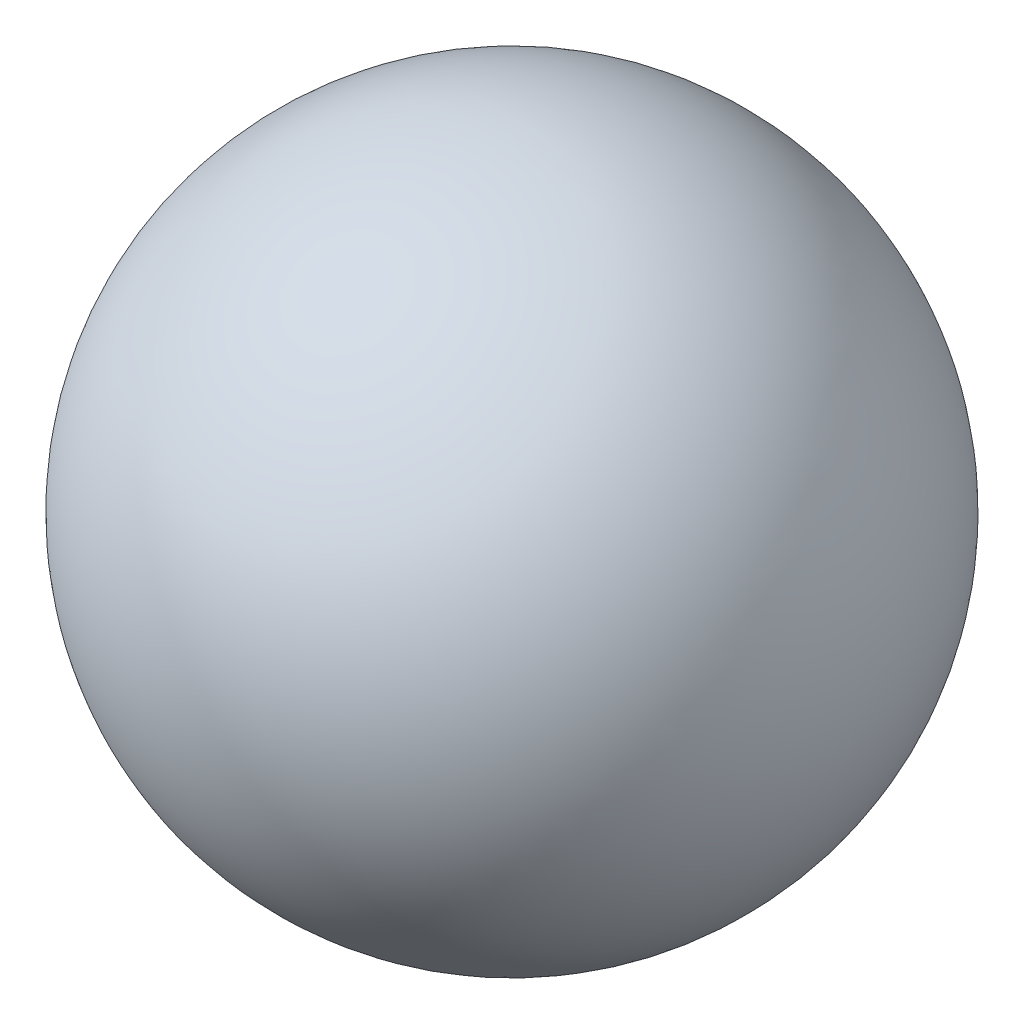
SolidWorks part; units mm, degrees
ref_plane "Front Plane" through (0, 0, 0) normal (0, 0, 1) x (1, 0, 0)
ref_plane "Top Plane" through (0, 0, 0) normal (0, 1, 0) x (1, 0, 0)
ref_plane "Right Plane" through (0, 0, 0) normal (1, 0, 0) x (0, 0, -1)
sketch "Sketch1" plane through (0, 0, 0) normal (0, 1, 0) x (1, 0, 0)
  line L0 (0, 7) -> (0, -7) construction
  circle A0 centre (0, 0) radius 7
  dimension "D1" = 14
revolve "Revolve2" add sketch "Sketch1" angle 360 about L0
